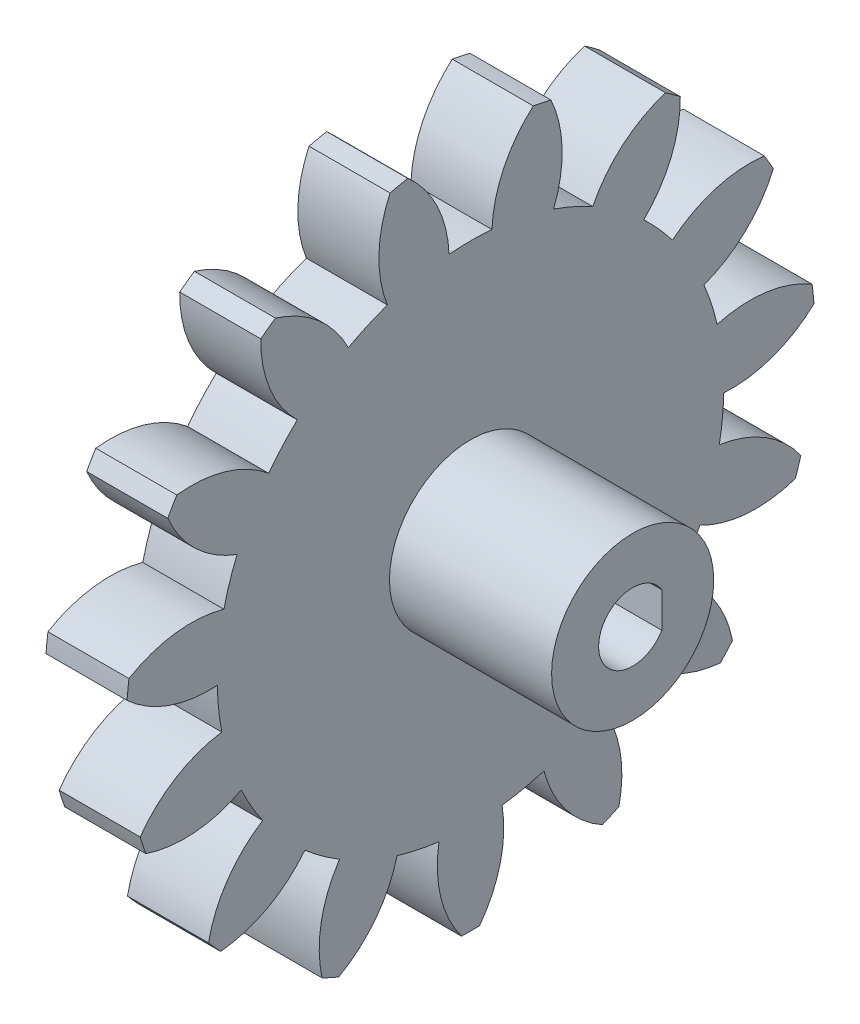
SolidWorks part; units mm, degrees
ref_plane "Plane1" through (0, 0, 0) normal (0, 0, 1) x (1, 0, 0)
ref_plane "Plane2" through (0, 0, 0) normal (0, 1, 0) x (1, 0, 0)
ref_plane "Plane3" through (0, 0, 0) normal (1, 0, 0) x (0, 0, -1)
sketch "HoldingSke" plane through (0, 0, 0) normal (0, 1, 0) x (1, 0, 0)
  line L0 (0, 0) -> (196.2761, -52.592)
  line L1 (-15, 0) -> (100, 0) construction
  line L2 (0, 0) -> (-2.1039, 2.3779)
  line L3 (0, 0) -> (-11.863, 4.5341)
  line L4 (0, 0) -> (8.3417, 2.2352)
  line L5 (0, 0) -> (-47.5972, -17.7524)
  line L6 (0, 0) -> (-5.2639, -3.5516)
  line L7 (-2.1039, 2.3779) -> (8.8308, 51.9871)
  line L8 (-76.2, 54.61) -> (-72.771, 54.61)
  line L9 (-71.009, 38.7566) -> (-53.1078, 45.2721)
  line L10 (-76.2, 71.12) -> (104.1128, 71.12)
  line L11 (0, 0) -> (-6.35, 0)
  line L12 (-76.2, 101.6) -> (-76.0857, 101.6)
  line L13 (24.9733, 27.94) -> (52.9518, 28.4284)
  line L14 (24.9733, 27.94) -> (24.9746, 27.94)
  line L15 (24.9733, 27.94) -> (100.4006, 29.5858)
  circle A0 centre (0, 0) radius 1.5875
  circle A1 centre (0, 0) radius 19.8425
  circle A2 centre (0, 0) radius 38.1
  circle A3 centre (0, 0) radius 1.5875
  dimension "MHD" = 39.685
  dimension "Hub_dia" = 76.2
  dimension "Bore" = 3.175
  dimension "MBD" = 3.175
  dimension "Num_teeth" = 15
  dimension "Pitch" = 203.2
  dimension "Overall_len" = 50.8
  dimension "Show_teeth" = 15
  dimension "Thickness" = 6.35
  dimension "OAL" = 50.8001
  dimension "T_dim" = 3.429
  dimension "Ap" = 20
  dimension "H" = 19.05
  dimension "Pitch_radius" = 180.3128
  dimension "Width" = 6.35
  dimension "Backlash" = 0.1143
  dimension "Addendum_fac" = 1
  dimension "Dedendum_fac" = 1.25
  dimension "Clearance_fac" = 0.25
  dimension "Dedendum_add" = 0.0013
sketch "BasProSke" plane through (0, 0, 0) normal (0, 1, 0) x (1, 0, 0)
  line L0 (-10, 0) -> (60, 0) construction
  line L1 (0, 0) -> (0, 26.9875)
  line L2 (0, 0) -> (6.35, 0)
  line L3 (6.35, 0) -> (6.35, 26.9875)
  line L4 (6.35, 26.9875) -> (0, 26.9875)
  dimension "Thickness" = 6.35
  dimension "Diameter" = 53.975
revolve "Base-Revolve" add sketch "BasProSke" angle 360 about L0
sketch "TooCutSke" plane through (0, 0, 0) normal (1, 0, 0) x (0, 0, -1)
  line L1 (0, 0) -> (0, 107) construction
  line L2 (0, 0) -> (-2.6889, 23.6602) construction
  line L3 (0, 0) -> (-9.8559, 46.3685) construction
  line L4 (-2.6889, 23.6602) -> (-4.928, 23.1843) construction
  arc A0 (1.6786, 19.7714) -> (-1.6786, 19.7714) centre (0, 0) ccw
  arc A1 (4.9398, 26.5574) -> (-4.9398, 26.5574) centre (0, 0) ccw
  circle A2 centre (0, 0) radius 23.8125 construction
  circle A3 centre (0, 0) radius 22.3764 construction
  arc A4 (-1.6786, 19.7714) -> (-4.9398, 26.5574) centre (-11.1953, 19.3745) ccw
  arc A5 (4.9398, 26.5574) -> (1.6786, 19.7714) centre (11.1953, 19.3745) ccw
  dimension "Root_dia" = 39.685
  dimension "Overcut_dia" = 54.0258
  dimension "Pitch_dia" = 47.625
  dimension "Base_dia" = 44.7529
  dimension "Flank_rad" = 9.525
  dimension "Half_ang" = 12
  dimension "Half_CT" = 2.2891
extrude "ToothCut" cut sketch "TooCutSke" along normal through all
fillet "Breaks" [suppressed] radius 0.0635
fillet "RootFillets" [suppressed] radius 0.795
pattern_circular "TeethCuts" count 15 over 360 about axis through (0, 0, 0) along (1, 0, 0) of "ToothCut", "RootFillets", "Breaks"
sketch "HubNeaOneSke" plane through (0, 0, 0) normal (-1, 0, 0) x (0, 0, 1)
  circle A0 centre (0, 0) radius 19.8425
  dimension "Diameter" = 39.685
extrude "HubNearOne" [suppressed] add sketch "HubNeaOneSke" along normal blind 44.4501
sketch "HubNeaBotSke" plane through (0, 0, 0) normal (-1, 0, 0) x (0, 0, 1)
  circle A0 centre (0, 0) radius 19.8425
  dimension "Diameter" = 39.685
extrude "HubNearBoth" [suppressed] add sketch "HubNeaBotSke" along normal blind 22.225
ref_plane "FarPln" through (6.35, 0, 0) normal (1, 0, 0) x (0, 0, -1)
sketch "HubFarSke" plane through (6.35, 0, 0) normal (1, 0, 0) x (0, 0, -1)
  circle A0 centre (0, 0) radius 19.8425
  dimension "Diameter" = 39.685
extrude "HubFar" [suppressed] add sketch "HubFarSke" along normal blind 22.225
sketch "BorSke" plane through (0, 0, 0) normal (1, 0, 0) x (0, 0, -1)
  circle A0 centre (0, 0) radius 1.5875
  dimension "Diameter" = 3.175
extrude "Bore" cut sketch "BorSke" along normal mid plane 101.6001
sketch "KeySke" plane through (0, 0, 0) normal (1, 0, 0) x (0, 0, -1)
  line L0 (-0.127, 0) -> (-0.127, 1.8415)
  line L1 (-0.127, 1.8415) -> (0.127, 1.8415)
  line L2 (0.127, 1.8415) -> (0.127, 0)
  line L3 (0, 0) -> (0, 34) construction
  line L4 (-0.127, 0) -> (0.127, 0)
  dimension "Offset" = 1.8415
  dimension "Width" = 0.254
extrude "Keyway" [suppressed] cut sketch "KeySke" along normal mid plane 101.6001
pattern_circular "Keyway2" [suppressed] count 2 every 90 about axis through (-10, 0, 0) along (1, 0, 0)
sketch "Sketch1" plane through (6.35, 0, 0) normal (1, 0, 0) x (0, 0, -1)
  circle A0 centre (0, 0) radius 6.35
  dimension "D1" = 12.7
extrude "Boss-Extrude1" add sketch "Sketch1" along normal blind 12.7
sketch "Sketch2" plane through (19.05, 0, 0) normal (1, 0, 0) x (0, 0, -1)
  line L0 (0, 2.667) -> (0, -2.667)
  line L1 (0, 0) -> (2.286, 0)
  line L2 (2.286, 2.9999) -> (2.286, -2.7173)
  circle A0 centre (0, 0) radius 2.667
  dimension "D1" = 5.334
  dimension "D2" = 2.286
extrude "Cut-Extrude1" cut sketch "Sketch2" against normal through all contours L2 A0 L0 L1 | L0 A0 | L0 A0 L2 L1
equation "' \"Pitch@HoldingSke\" = 4"
equation "' \"Num_teeth@HoldingSke\" = 12"
equation "' \"Ap@HoldingSke\" =  20"
equation "' \"Ap@HoldingSke\" = 20"
equation "' \"Width@HoldingSke\" = 0.5"
equation "' \"Hub_dia@HoldingSke\"= 1"
equation "' \"Hub_dia@HoldingSke\" = 1"
equation "' \"Overall_len@HoldingSke\" = 1.0"
equation "' \"Bore@HoldingSke\" = 0.75"
equation "' \"T_dim@HoldingSke\" = 0.85"
equation "' \"Width@KeySke\" = 0.25"
equation "' \"Show_teeth@HoldingSke\" = 13"
equation "' \"Backlash@HoldingSke\" = 0.009"
equation "' \"Addendum_fac@HoldingSke\" = 1.0"
equation "' \"Dedendum_fac@HoldingSke\" = 1.25"
equation "' \"Dedendum_add@HoldingSke\" = 0.00005"
equation "' \"Clearance_fac@HoldingSke\" = 0.25"
equation "' \"Pitch@HoldingSke\" = 0.5"
equation "' \"Num_teeth@HoldingSke\" = 23"
equation "' \"Show_teeth@HoldingSke\" = 23"
equation "' \"Backlash@HoldingSke\" = 0.0375"
equation "\"Overcut_dia@TooCutSke\" = (\"Num_teeth@HoldingSke\" + 2 * \"Addendum_fac@HoldingSke\") / \"Pitch@HoldingSke\" + 0.002"
equation "\"Pitch_dia@TooCutSke\" = \"Num_teeth@HoldingSke\" / \"Pitch@HoldingSke\""
equation "\"Base_dia@TooCutSke\" = \"Num_teeth@HoldingSke\" / \"Pitch@HoldingSke\" * cos((\"Ap@HoldingSke\"  * 3.14159265 / 180))"
equation "\"Root_dia@TooCutSke\" = (\"Num_teeth@HoldingSke\" + 2) / \"Pitch@HoldingSke\" - 2 * (\"Addendum_fac@HoldingSke\" + \"Dedendum_fac@HoldingSke\") / \"Pitch@HoldingSke\" - \"Dedendum_add@HoldingSke\" * 2"
equation "\"Half_ang@TooCutSke\" = 180 / \"Num_teeth@HoldingSke\""
equation "\"Half_CT@TooCutSke\" = \"Num_teeth@HoldingSke\" / \"Pitch@HoldingSke\" * sin((3.14159265 / 2 / \"Num_teeth@HoldingSke\")) / 2 - 7 * \"Backlash@HoldingSke\" / 4"
equation "\"Flank_rad@TooCutSke\" = \"Num_teeth@HoldingSke\" / \"Pitch@HoldingSke\" / 5"
equation "\"Radius@RootFillets\" = \"Clearance_fac@HoldingSke\" / \"Pitch@HoldingSke\" + \"Dedendum_add@HoldingSke\""
equation "\"Break_rad@Breaks\" = 0.02 / \"Pitch@HoldingSke\""
equation "\"Thickness@HoldingSke\" = \"Width@HoldingSke\""
equation "\"OAL@HoldingSke\" = \"Thickness@HoldingSke\""
equation "\"MHD@HoldingSke\" = (\"Num_teeth@HoldingSke\" + 2) / \"Pitch@HoldingSke\" - 2 * (\"Addendum_fac@HoldingSke\" + \"Dedendum_fac@HoldingSke\")  / \"Pitch@HoldingSke\" - \"Dedendum_add@HoldingSke\" * 2"
equation "\"MBD@HoldingSke\" = (\"Num_teeth@HoldingSke\" + 2) / \"Pitch@HoldingSke\" - 2 * (\"Addendum_fac@HoldingSke\" + \"Dedendum_fac@HoldingSke\")  / \"Pitch@HoldingSke\" - \"Dedendum_add@HoldingSke\" * 2 - 0.002"
equation "\"MHD@HoldingSke\" = ((sgn( \"MHD@HoldingSke\" - \"Hub_dia@HoldingSke\" )-1)*( \"MHD@HoldingSke\" - \"Hub_dia@HoldingSke\" ))/-2+ \"Hub_dia@HoldingSke\""
equation "\"MBD@HoldingSke\" = ((sgn( \"MBD@HoldingSke\" - \"Bore@HoldingSke\" )-1)*( \"MBD@HoldingSke\" - \"Bore@HoldingSke\" ))/-2+ \"Bore@HoldingSke\""
equation "\"OAL@HoldingSke\" = ((sgn( \"OAL@HoldingSke\" - \"Overall_len@HoldingSke\" )+1)*( \"OAL@HoldingSke\" - \"Overall_len@HoldingSke\" ))/2 + \"Overall_len@HoldingSke\" + 0.000002"
equation "\"Num_teeth@TeethCuts\" = int( \"Show_teeth@HoldingSke\" ) + 1"
equation "\"Num_teeth@TeethCuts\" = ((sgn( \"Num_teeth@TeethCuts\" - \"Num_teeth@HoldingSke\" )-1)*( \"Num_teeth@TeethCuts\" - \"Num_teeth@HoldingSke\" ))/-2+ \"Num_teeth@HoldingSke\""
equation "\"Num_teeth@TeethCuts\" = ((sgn( \"Num_teeth@TeethCuts\" - 2.0)+1)*( \"Num_teeth@TeethCuts\" - 2.0))/2 +2.0"
equation "\"Angle@TeethCuts\" = 360.0 / \"Num_teeth@HoldingSke\""
equation "\"Diameter@BasProSke\" = (\"Num_teeth@HoldingSke\" + 2 * \"Addendum_fac@HoldingSke\") / \"Pitch@HoldingSke\""
equation "\"Thickness@BasProSke\"  = \"Thickness@HoldingSke\""
equation "' \"Fillet_rad@BasProSke\" =  \"Thickness@HoldingSke\" * 0.05"
equation "' \"Fillet_rad@BasProSke\" = \"Thickness@HoldingSke\" * 0.05"
equation "\"MHD@HoldingSke\" = ((sgn( \"MHD@HoldingSke\" - \"Root_dia@TooCutSke\" )-1)*( \"MHD@HoldingSke\" - \"Root_dia@TooCutSke\" ))/-2+ \"Root_dia@TooCutSke\""
equation "\"Diameter@HubNeaOneSke\" = \"MHD@HoldingSke\""
equation "\"Length@HubNearOne\" = \"OAL@HoldingSke\" - \"Thickness@BasProSke\""
equation "\"Diameter@HubNeaBotSke\" = \"MHD@HoldingSke\""
equation "\"Length@HubNearBoth\" = ( \"OAL@HoldingSke\" - \"Thickness@BasProSke\" ) / 2.0"
equation "\"Thickness@FarPln\" = \"Thickness@BasProSke\""
equation "\"Diameter@HubFarSke\" = \"MHD@HoldingSke\""
equation "\"Length@HubFar\" = ( \"OAL@HoldingSke\" - \"Thickness@BasProSke\" ) / 2.0"
equation "\"Diameter@BorSke\" = \"MBD@HoldingSke\""
equation "\"D1@Bore\" = \"OAL@HoldingSke\" * 2.0"
equation "\"D1@Keyway\" = \"OAL@HoldingSke\" * 2.0"
equation "\"Offset@KeySke\" = \"T_dim@HoldingSke\" - \"MBD@HoldingSke\" / 2.0"
